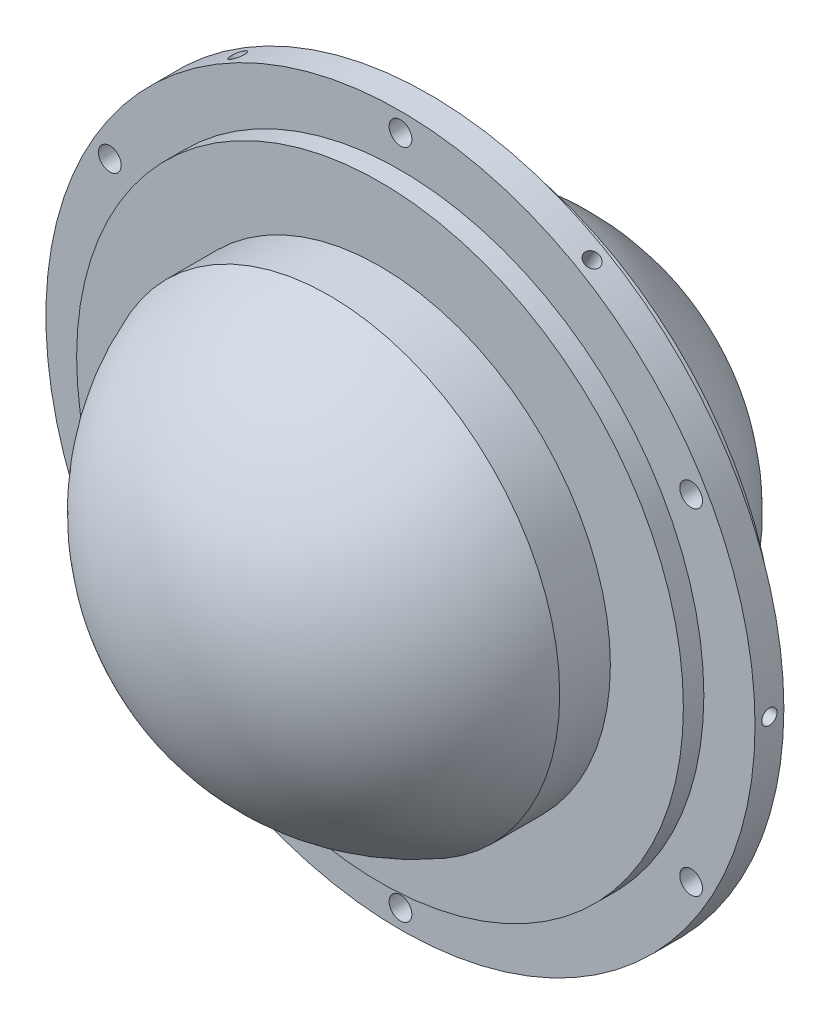
SolidWorks part; units mm, degrees
ref_plane "Front Plane" through (0, 0, 0) normal (0, 0, 1) x (1, 0, 0)
ref_plane "Top Plane" through (0, 0, 0) normal (0, 1, 0) x (1, 0, 0)
ref_plane "Right Plane" through (0, 0, 0) normal (1, 0, 0) x (0, 0, -1)
sketch "Sketch1" plane through (0, 0, 0) normal (1, 0, 0) x (0, 0, -1)
  line L0 (0, 0) -> (156.1593, 0) construction
  line L1 (64.8, 0) -> (-64.8, 0)
  line L2 (22.5494, 60.75) -> (16.31, 60.75)
  line L3 (16.31, 60.75) -> (16.31, 70)
  line L4 (16.31, 70) -> (11.41, 70)
  line L5 (11.41, 70) -> (11.41, 84)
  line L6 (11.41, 84) -> (3.81, 84)
  line L7 (3.81, 84) -> (3.81, 93.5)
  line L8 (3.81, 93.5) -> (-3.79, 93.5)
  line L9 (-3.79, 93.5) -> (-3.79, 80)
  line L10 (-3.79, 80) -> (-9.19, 80)
  line L11 (-9.19, 80) -> (-9.19, 60.75)
  line L12 (-9.19, 60.75) -> (-22.5494, 60.75)
  arc A0 (22.5494, 60.75) -> (64.8, 0) centre (0, 0) cw
  arc A1 (-64.8, 0) -> (-22.5494, 60.75) centre (0, 0) cw
  point P2 (0, 0)
  dimension "D1" = 129.6
  dimension "D2" = 3.81
  dimension "D3" = 25.5
  dimension "D4" = 7.6
  dimension "D5" = 7.6
  dimension "D6" = 12.5
  dimension "D7" = 160
  dimension "D8" = 187
  dimension "D9" = 168
  dimension "D10" = 121.5
  dimension "D11" = 121.5
  dimension "D12" = 140
revolve "Revolve1" add sketch "Sketch1" angle 360 about L0
sketch "Sketch6" plane through (0, 0, 0) normal (1, 0, 0) x (0, 0, -1)
  circle A0 centre (0, 0) radius 2
  dimension "D1" = 4
extrude "Cut-Extrude1" cut sketch "Sketch6" against normal through all from offset 80 offset against normal yes
sketch "Sketch7" plane through (0, 0, -3.81) normal (0, 0, -1) x (-1, 0, 0)
  circle A0 centre (0, 88.5) radius 3
  dimension "D2" = 6
  dimension "D1" = 88.5
extrude "Cut-Extrude2" cut sketch "Sketch7" against normal through all
pattern_circular "CirPattern1" count 6 over 360 about axis through (0, 0, 0) along (0, 0, 1) of "Cut-Extrude2", "Cut-Extrude1"
